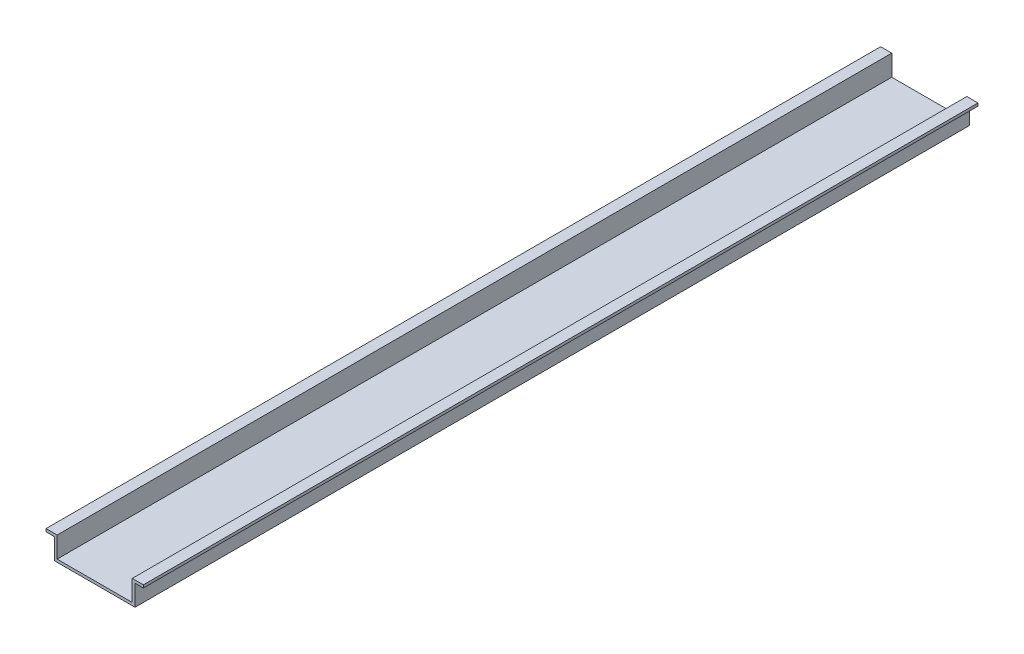
SolidWorks part; units mm, degrees
ref_plane "Front Plane" through (0, 0, 0) normal (0, 0, 1) x (1, 0, 0)
ref_plane "Top Plane" through (0, 0, 0) normal (0, 1, 0) x (1, 0, 0)
ref_plane "Right Plane" through (0, 0, 0) normal (1, 0, 0) x (0, 0, -1)
sketch "Sketch1" plane through (0, 0, 0) normal (0, 0, 1) x (1, 0, 0)
  line L0 (0, 0) -> (0, 18.2991) construction
  line L1 (13.5, 0) -> (-13.5, 0)
  line L2 (-13.5, 0) -> (-13.5, 7.5)
  line L3 (-13.5, 7.5) -> (-17.5, 7.5)
  line L4 (13.5, 7.5) -> (17.5, 7.5)
  line L5 (13.5, 0) -> (13.5, 7.5)
  point P9 (0, 0)
  dimension "D1" = 35
  dimension "D2" = 27
  dimension "D3" = 7.5
extrude "Extrude-Thin1" add sketch "Sketch1" along normal mid plane 300 thin thin type one direction wall 1
